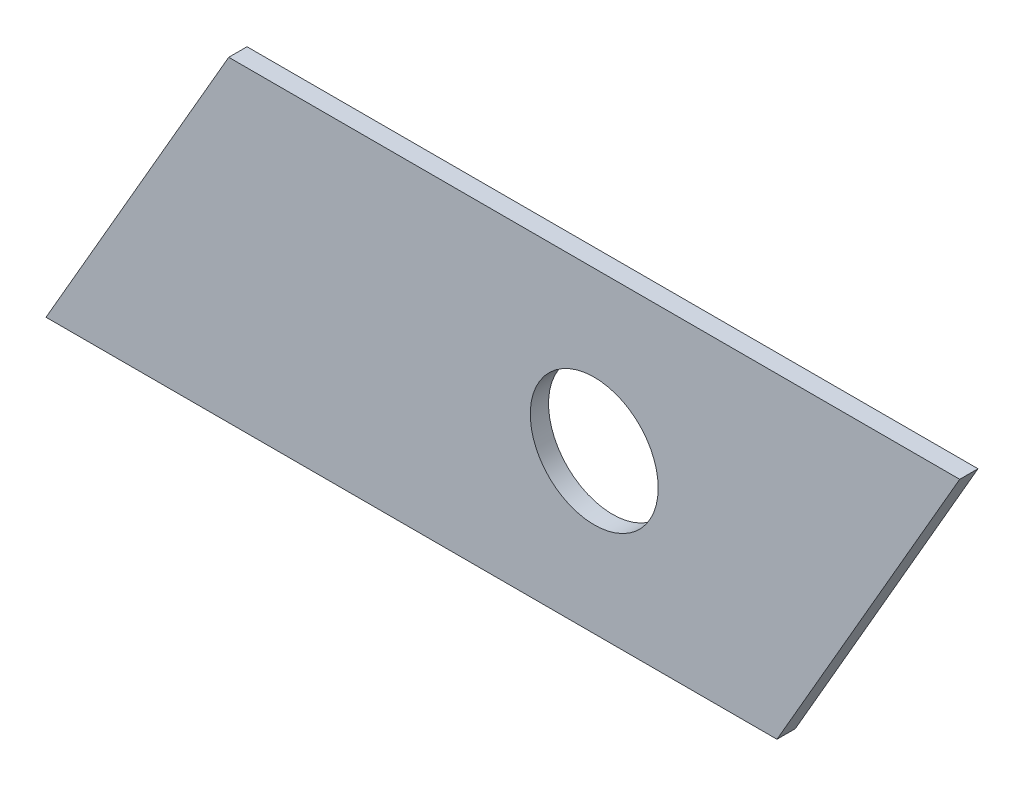
SolidWorks part; units mm, degrees
ref_plane "前视基准面" through (0, 0, 0) normal (0, 0, 1) x (1, 0, 0)
ref_plane "上视基准面" through (0, 0, 0) normal (0, 1, 0) x (1, 0, 0)
ref_plane "右视基准面" through (0, 0, 0) normal (1, 0, 0) x (0, 0, -1)
sketch "草图3" plane through (0, 0, 0) normal (0, 0, 1) x (1, 0, 0)
  line L0 (0, 0) -> (5, 8.6603)
  line L1 (5, 8.6603) -> (-15, 8.6603)
  line L2 (-15, 8.6603) -> (-20, 0)
  line L3 (-20, 0) -> (0, 0)
  line L4 (-17.5, 4.3301) -> (-14.1857, 4.3301)
  circle A1 centre (-5, 4.3301) radius 1.75
  dimension "D3" = 3.5
  dimension "D5" = 5
  dimension "D1" = 60
  dimension "D2" = 60
  dimension "D4" = 20
  dimension "D6" = 20
  dimension "D7" = 10
extrude "凸台-拉伸1" add sketch "草图3" along normal blind 0.5
